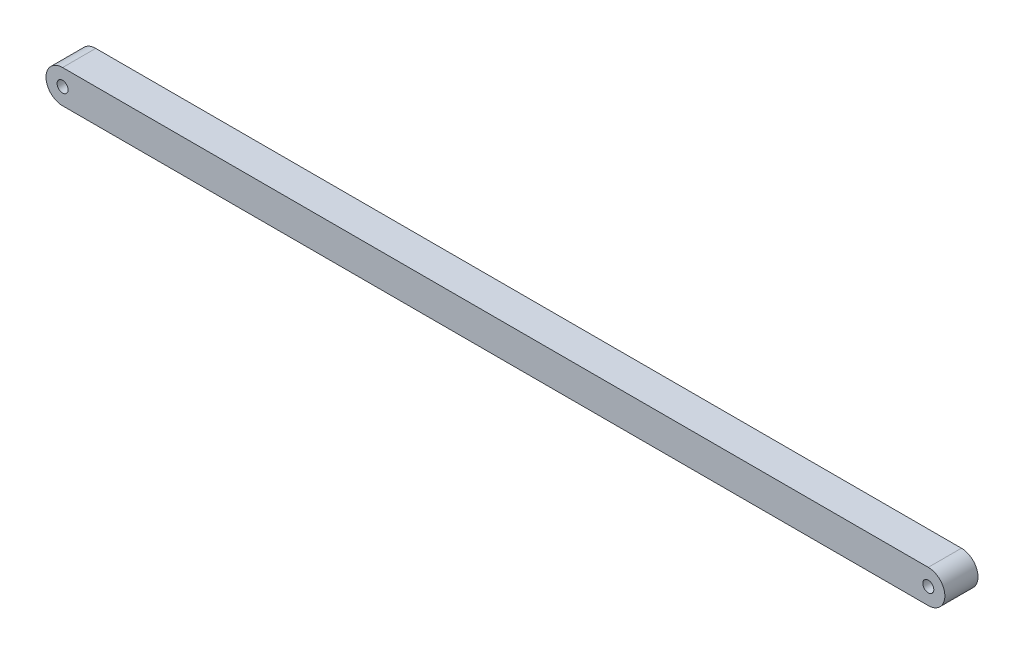
SolidWorks part; units mm, degrees
ref_plane "Front" through (0, 0, 0) normal (0, 0, 1) x (1, 0, 0)
ref_plane "Top" through (0, 0, 0) normal (0, 1, 0) x (1, 0, 0)
ref_plane "Right" through (0, 0, 0) normal (1, 0, 0) x (0, 0, -1)
sketch "Sketch1" plane through (0, 0, 0) normal (0, 0, 1) x (1, 0, 0)
  line L0 (0, 0) -> (4.5, 0) construction
  line L1 (0, 4.5) -> (235, 4.5)
  line L2 (0, -4.5) -> (235, -4.5)
  line L3 (4.5, 0) -> (230.5, 0) construction
  line L4 (230.5, 0) -> (235, 0) construction
  circle A0 centre (0, 0) radius 1.5
  circle A1 centre (235, 0) radius 1.5
  arc A2 (0, 4.5) -> (0, -4.5) centre (0, 0) ccw
  arc A3 (235, -4.5) -> (235, 4.5) centre (235, 0) ccw
  arc A4 (4.5, 0) -> (0, 4.5) centre (0, 0) ccw construction
  circle A5 centre (0, 0) radius 4.5 construction
  arc A6 (0, -4.5) -> (4.5, 0) centre (0, 0) ccw construction
  arc A7 (235, 4.5) -> (230.5, 0) centre (235, 0) ccw construction
  circle A8 centre (235, 0) radius 4.5 construction
  arc A9 (230.5, 0) -> (235, -4.5) centre (235, 0) ccw construction
  dimension "D2" = 3
  dimension "D1" = 235
  dimension "D3" = 3
  dimension "D4" = 3
extrude "Boss-Extrude1" add sketch "Sketch1" along normal blind 9
